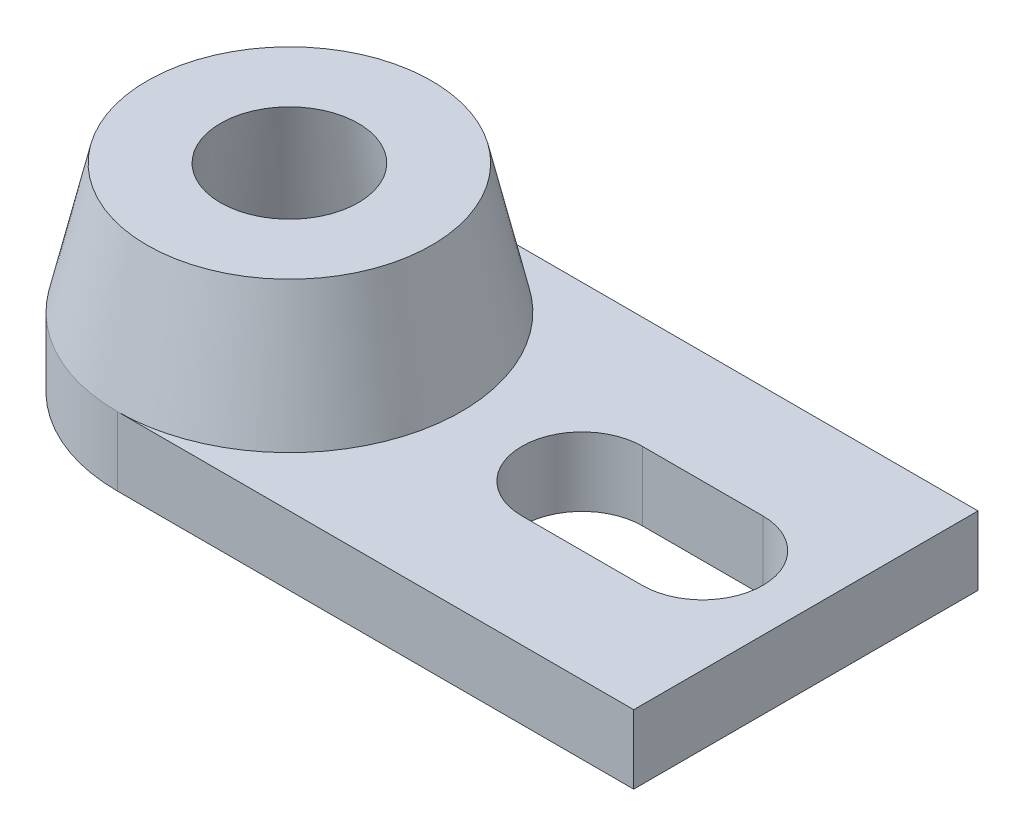
SolidWorks part; units mm, degrees
ref_plane "Alzado" through (0, 0, 0) normal (0, 0, 1) x (1, 0, 0)
ref_plane "Planta" through (0, 0, 0) normal (0, 1, 0) x (1, 0, 0)
ref_plane "Vista lateral" through (0, 0, 0) normal (1, 0, 0) x (0, 0, -1)
sketch "Croquis1" plane through (0, 0, 0) normal (0, 1, 0) x (1, 0, 0)
  line L0 (0, 20) -> (60, 20)
  line L1 (60, 20) -> (60, -20)
  line L2 (60, -20) -> (0, -20)
  line L3 (-20, 0) -> (60, 0) construction
  line L4 (48, 0) -> (34, 0) construction
  line L5 (48, -7) -> (34, -7)
  line L6 (48, 7) -> (34, 7)
  arc A0 (0, 20) -> (0, -20) centre (0, 0) ccw
  arc A1 (48, -7) -> (48, 7) centre (48, 0) ccw
  arc A2 (34, 7) -> (34, -7) centre (34, 0) ccw
  point P10 (41, 0)
  dimension "D1" = 40
  dimension "D2" = 80
  dimension "D5" = 7
  dimension "D3" = 12
  dimension "D4" = 14
extrude "Saliente-Extruir1" add sketch "Croquis1" along normal blind 8
sketch "Croquis2" plane through (0, 8, 0) normal (0, 1, 0) x (1, 0, 0)
  line L3 (0, -20) -> (60, -20)
  line L4 (60, -20) -> (60, 20)
  line L5 (60, 20) -> (0, 20)
  circle A0 centre (0, 0) radius 20
  arc A1 (0, 20) -> (0, -20) centre (0, 0) ccw
  arc A2 (0, 20) -> (0, -20) centre (0, 0) ccw
  arc M6 (0, 20) -> (0, -20) centre (0, 0) ccw
  dimension "D1" = 0
extrude "Saliente-Extruir2" add sketch "Croquis2" along normal blind 15 draft 13 contours A0 M6
sketch "Croquis3" plane through (0, 23, 0) normal (0, 1, 0) x (1, 0, 0)
  circle A0 centre (0, 0) radius 8
  point P1 (0, 0)
  dimension "D2" = 16
extrude "Cortar-Extruir1" cut sketch "Croquis3" against normal through all draft 10 draft outward yes
